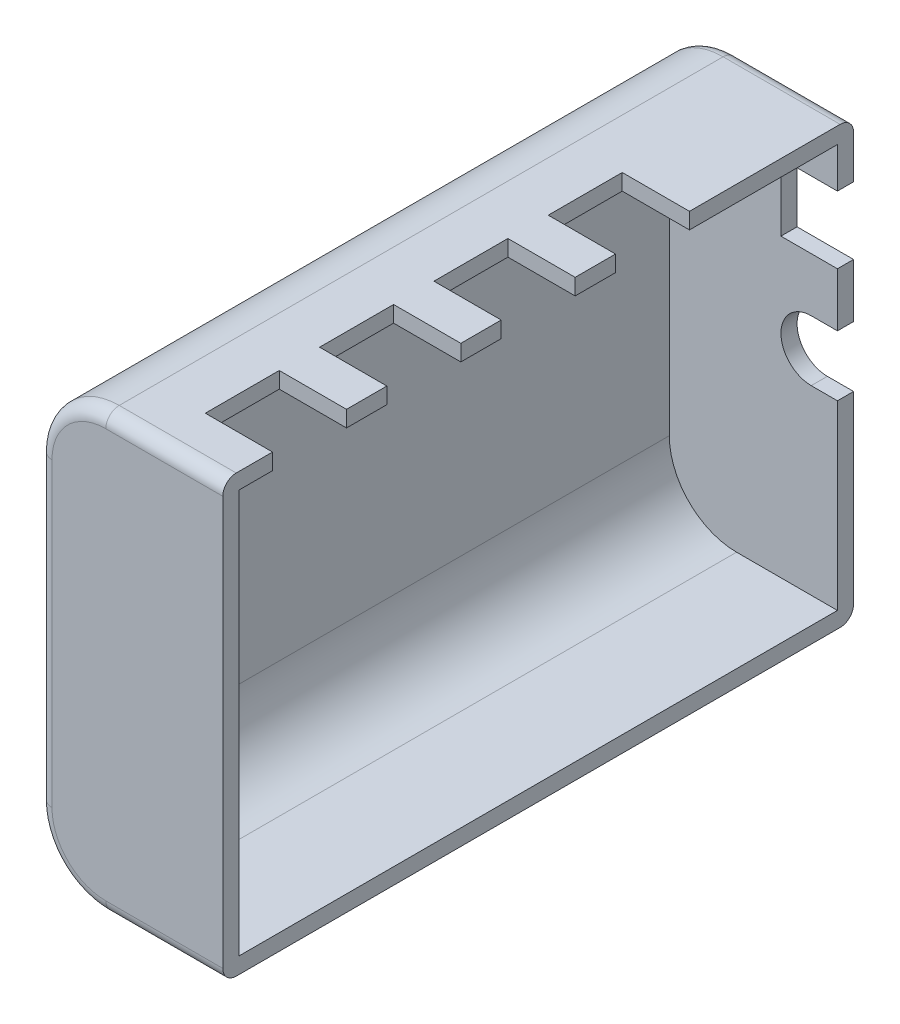
SolidWorks part; units mm, degrees
ref_plane "Front Plane" through (0, 0, 0) normal (0, 0, 1) x (1, 0, 0)
ref_plane "Top Plane" through (0, 0, 0) normal (0, 1, 0) x (1, 0, 0)
ref_plane "Right Plane" through (0, 0, 0) normal (1, 0, 0) x (0, 0, -1)
sketch "Sketch1" plane through (16.0375, 0, 0) normal (-1, 0, 0) x (0, 0, 1)
  line L1 (13.6383, 39.8092) -> (58.1383, 39.8092)
  line L2 (13.6383, 39.8092) -> (13.6383, 9.8092)
  line L3 (13.6383, 9.8092) -> (58.1383, 9.8092)
  line L4 (58.1383, 39.8092) -> (58.1383, 9.8092)
  point P6 (0, 0)
  point P7 (0, 0)
  point P8 (0, 0)
  point P9 (0, 0)
  point P11 (0, 0)
  point P12 (0, 0)
extrude "Boss-Extrude1" add sketch "Sketch1" along normal blind 12.5
shell "Shell1" thickness 1.2
sketch "Sketch2" plane through (0, 41.0092, 0) normal (0, 1, 0) x (1, 0, 0)
  line L0 (16.0375, -55.6383) -> (21.0375, -55.6383) construction
  line L1 (16.0375, -55.6383) -> (21.0375, -55.6383) construction
  line L2 (21.0375, -50.1383) -> (16.0375, -50.1383) construction
  line L3 (21.0375, -50.1383) -> (16.0375, -50.1383) construction
  line L4 (16.0375, -59.3383) -> (16.0375, -12.4383)
  line L5 (16.0375, -12.4383) -> (2.3375, -12.4383)
  line L6 (2.3375, -12.4383) -> (2.3375, -59.3383)
  line L7 (2.3375, -59.3383) -> (16.0375, -59.3383)
  line L8 (16.0375, -59.3383) -> (16.0375, -12.4383)
  line L9 (16.0375, -12.4383) -> (2.3375, -12.4383)
  line L10 (2.3375, -12.4383) -> (2.3375, -59.3383)
  line L11 (2.3375, -59.3383) -> (16.0375, -59.3383)
  line L12 (21.0375, -41.6383) -> (16.0375, -41.6383) construction
  line L13 (21.0375, -41.6383) -> (16.0375, -41.6383) construction
  line L14 (16.0375, -47.1383) -> (21.0375, -47.1383) construction
  line L15 (16.0375, -47.1383) -> (21.0375, -47.1383) construction
  line L16 (16.0375, -38.6383) -> (21.0375, -38.6383) construction
  line L17 (16.0375, -38.6383) -> (21.0375, -38.6383) construction
  line L18 (21.0375, -33.1383) -> (16.0375, -33.1383) construction
  line L19 (21.0375, -33.1383) -> (16.0375, -33.1383) construction
  line L20 (16.0375, -30.1383) -> (21.0375, -30.1383) construction
  line L21 (16.0375, -30.1383) -> (21.0375, -30.1383) construction
  line L22 (21.0375, -24.6383) -> (16.0375, -24.6383) construction
  line L23 (21.0375, -24.6383) -> (16.0375, -24.6383) construction
  line L24 (16.0375, -55.6383) -> (11.0375, -55.6383)
  line L25 (11.0375, -55.6383) -> (11.0375, -50.1383)
  line L26 (11.0375, -50.1383) -> (16.0375, -50.1383)
  line L27 (16.0375, -47.1383) -> (11.0375, -47.1383)
  line L28 (11.0375, -47.1383) -> (11.0375, -41.6383)
  line L29 (11.0375, -41.6383) -> (16.0375, -41.6383)
  line L30 (16.0375, -38.6383) -> (11.0375, -38.6383)
  line L31 (11.0375, -38.6383) -> (11.0375, -33.1383)
  line L32 (11.0375, -33.1383) -> (16.0375, -33.1383)
  line L33 (16.0375, -30.1383) -> (11.0375, -30.1383)
  line L34 (11.0375, -30.1383) -> (11.0375, -24.6383)
  line L35 (11.0375, -24.6383) -> (16.0375, -24.6383)
  line L36 (16.0375, -30.1383) -> (16.0375, -24.6383)
  line L37 (16.0375, -38.6383) -> (16.0375, -33.1383)
  line L38 (16.0375, -47.1383) -> (16.0375, -41.6383)
  line L39 (16.0375, -55.6383) -> (16.0375, -50.1383)
  dimension "D1" = 0
extrude "Cut-Extrude1" cut sketch "Sketch2" against normal up to surface (1.2 mm away) contours L26 L25 L24 L8 | L29 L28 L27 L8 | L32 L31 L30 L8 | L35 L34 L33 L8 up to face at (9.7875, 39.8092, 35.8883)
sketch "Sketch3" plane through (0, 0, 12.4383) normal (0, 0, -1) x (-1, 0, 0)
  line L1 (-16.0375, 36.8092) -> (-20.2375, 36.8092) construction
  line L3 (-20.2375, 31.8092) -> (-16.0375, 31.8092) construction
  line L5 (-16.0375, 27.8092) -> (-17.9875, 27.8092) construction
  line L7 (-17.9875, 23.3092) -> (-16.0375, 23.3092) construction
  line L8 (-16.0375, 36.8092) -> (-11.8375, 36.8092)
  line L9 (-11.8375, 36.8092) -> (-11.8375, 31.8092)
  line L10 (-11.8375, 31.8092) -> (-16.0375, 31.8092)
  line L11 (-16.0375, 31.8092) -> (-16.0375, 36.8092)
  line L12 (-16.0375, 27.8092) -> (-14.0875, 27.8092)
  line L13 (-16.0375, 23.3092) -> (-14.0875, 23.3092)
  line L14 (-16.0375, 27.8092) -> (-16.0375, 23.3092)
  line L15 (-16.0375, 36.8092) -> (-20.2375, 36.8092) construction
  line L16 (-20.2375, 31.8092) -> (-16.0375, 31.8092) construction
  line L17 (-16.0375, 36.8092) -> (-20.2375, 36.8092) construction
  line L18 (-16.0375, 41.0092) -> (-16.0375, 8.6092) construction
  line L19 (-16.0375, 27.8092) -> (-17.9875, 27.8092) construction
  line L20 (-17.9875, 23.3092) -> (-16.0375, 23.3092) construction
  arc A0 (-14.0875, 27.8092) -> (-14.0875, 23.3092) centre (-14.0875, 25.5592) cw
  point P17 (0, 0)
  point P18 (-19.3939, 36.8092)
  point P22 (0, 0)
  point P23 (-19.4361, 31.8092)
  point P25 (-16.0375, 36.8092)
  point P28 (-16.0375, 36.8092)
  point P29 (-16.0375, 36.8092)
  point P34 (-17.0125, 23.3092)
  point P36 (-17.9875, 27.8092)
  point P37 (-17.9875, 27.8092)
  point P38 (0, 0)
  point P39 (-17.9875, 27.8092)
  point P40 (-17.9875, 25.5592)
  point P42 (0, 0)
  point P43 (-17.9875, 27.8092)
  point P44 (-11.4048, 27.8092)
extrude "Cut-Extrude2" cut sketch "Sketch3" against normal up to surface (1.2 mm away) up to face at (9.7875, 24.8092, 13.6383)
fillet "Fillet1" radius 5 4 edges at (3.5375, 9.8092, 35.8883) (3.5375, 39.8092, 35.8883) (2.3375, 8.6092, 35.8883) (2.3375, 41.0092, 35.8883)
fillet "Fillet2" radius 1 10 edges at (11.6875, 8.6092, 59.3383) (3.802, 10.0737, 59.3383) (11.6875, 41.0092, 59.3383) (3.802, 39.5447, 59.3383) (11.6875, 8.6092, 12.4383) (3.802, 10.0737, 12.4383) (2.3375, 24.8092, 12.4383) (3.802, 39.5447, 12.4383) (2.3375, 24.8092, 59.3383) (11.6875, 41.0092, 12.4383)
